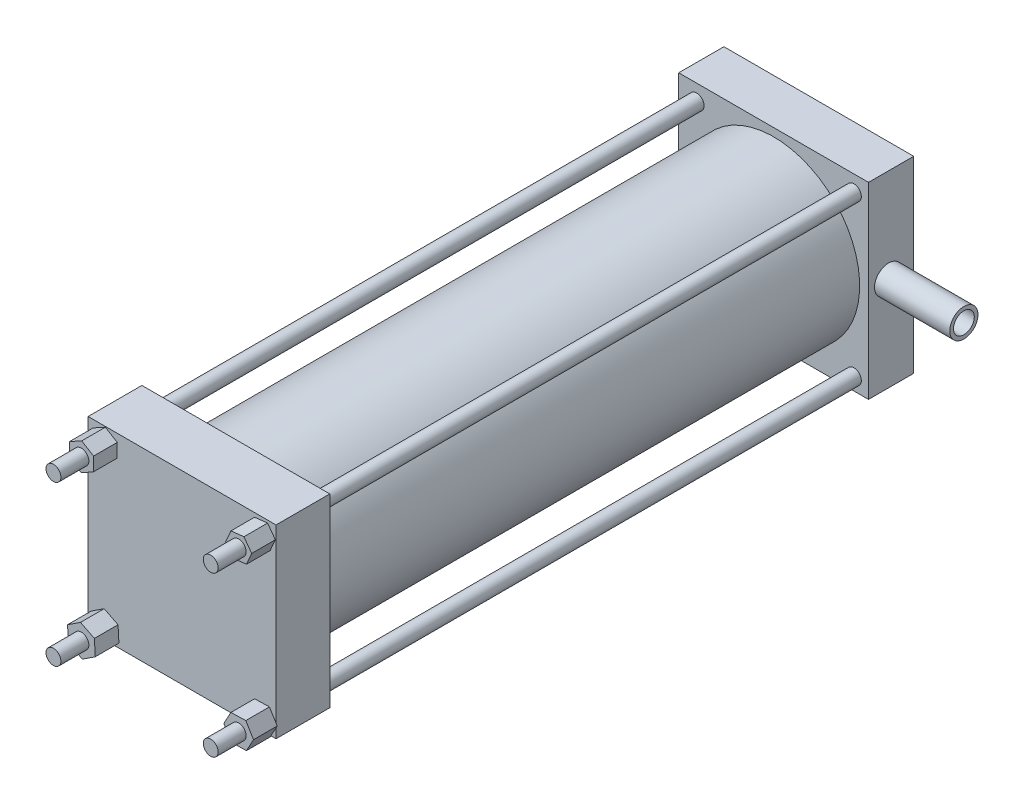
SolidWorks part; units mm, degrees
ref_plane "Front Plane" through (0, 0, 0) normal (0, 0, 1) x (1, 0, 0)
ref_plane "Top Plane" through (0, 0, 0) normal (0, 1, 0) x (1, 0, 0)
ref_plane "Right Plane" through (0, 0, 0) normal (1, 0, 0) x (0, 0, -1)
sketch "Sketch1" plane through (0, 0, 0) normal (0, 0, 1) x (1, 0, 0)
  circle A0 centre (0, 0) radius 30
  circle A1 centre (0, 0) radius 40
  dimension "D1" = 60
  dimension "D2" = 80
extrude "Boss-Extrude1" add sketch "Sketch1" along normal blind 250
ref_plane "Plane1" through (0, 0, 250) normal (0, 0, 1) x (1, 0, 0)
sketch "Sketch2" plane through (0, 0, 250) normal (0, 0, 1) x (1, 0, 0)
  line L1 (-43.6727, 43.0513) -> (43.6727, 43.0513)
  line L2 (-43.6727, 43.0513) -> (-43.6727, -43.0513)
  line L3 (-43.6727, -43.0513) -> (43.6727, -43.0513)
  line L4 (43.6727, 43.0513) -> (43.6727, -43.0513)
  line L5 (-43.6727, 43.0513) -> (43.6727, -43.0513) construction
  line L6 (-43.6727, -43.0513) -> (43.6727, 43.0513) construction
  point P0 (0, 0)
extrude "Boss-Extrude2" add sketch "Sketch2" along normal blind 25
ref_plane "Plane2" through (0, 0, 0) normal (0, 0, -1) x (-1, 0, 0)
sketch "Sketch3" plane through (0, 0, 0) normal (0, 0, -1) x (-1, 0, 0)
  line L1 (-44.1151, 43.6989) -> (44.1151, 43.6989)
  line L2 (-44.1151, 43.6989) -> (-44.1151, -43.6989)
  line L3 (-44.1151, -43.6989) -> (44.1151, -43.6989)
  line L4 (44.1151, 43.6989) -> (44.1151, -43.6989)
  line L5 (-44.1151, 43.6989) -> (44.1151, -43.6989) construction
  line L6 (-44.1151, -43.6989) -> (44.1151, 43.6989) construction
  circle A0 centre (0, 0) radius 15.0552
  point P0 (0, 0)
extrude "Boss-Extrude3" add sketch "Sketch3" along normal blind 21
sketch "Sketch4" plane through (44.1151, 0, 0) normal (1, 0, 0) x (0, 0, -1)
  circle A0 centre (9.3389, 0) radius 6.5589
  circle A1 centre (9.3389, 0) radius 4.8368
extrude "Boss-Extrude4" add sketch "Sketch4" along normal blind 35
sketch "Sketch5" plane through (0, 0, -21) normal (0, 0, -1) x (-1, 0, 0)
  circle A0 centre (-37.3178, 36.2685) radius 3.4633
  circle A1 centre (35.7964, 36.2685) radius 3.4633
  circle A2 centre (35.7964, -37.8077) radius 3.4633
  circle A3 centre (-37.3178, -37.8077) radius 3.4633
extrude "Boss-Extrude5" add sketch "Sketch5" against normal blind 320
sketch "Sketch6" plane through (0, 0, 275) normal (0, 0, 1) x (1, 0, 0)
  line L1 (-30.2671, 32.9214) -> (-30.1331, 39.3835)
  line L2 (-30.1331, 39.3835) -> (-35.6625, 42.7306)
  line L3 (-35.6625, 42.7306) -> (-41.3258, 39.6156)
  line L4 (-41.3258, 39.6156) -> (-41.4597, 33.1535)
  line L5 (-41.4597, 33.1535) -> (-35.9304, 29.8064)
  line L6 (-35.9304, 29.8064) -> (-30.2671, 32.9214)
  line L7 (40.9306, 31.3639) -> (43.3717, 36.945)
  line L8 (43.3717, 36.945) -> (39.7589, 41.8495)
  line L9 (39.7589, 41.8495) -> (33.705, 41.1731)
  line L10 (33.705, 41.1731) -> (31.2639, 35.592)
  line L11 (31.2639, 35.592) -> (34.8767, 30.6875)
  line L12 (34.8767, 30.6875) -> (40.9306, 31.3639)
  line L13 (-29.3509, -41.0426) -> (-29.7722, -33.8432)
  line L14 (-29.7722, -33.8432) -> (-36.2177, -30.6083)
  line L15 (-36.2177, -30.6083) -> (-42.2419, -34.5729)
  line L16 (-42.2419, -34.5729) -> (-41.8207, -41.7723)
  line L17 (-41.8207, -41.7723) -> (-35.3751, -45.0072)
  line L18 (-35.3751, -45.0072) -> (-29.3509, -41.0426)
  line L19 (40.9306, -43.6989) -> (44.2261, -37.6246)
  line L20 (44.2261, -37.6246) -> (40.6133, -31.7334)
  line L21 (40.6133, -31.7334) -> (33.705, -31.9166)
  line L22 (33.705, -31.9166) -> (30.4095, -37.9909)
  line L23 (30.4095, -37.9909) -> (34.0223, -43.8821)
  line L24 (34.0223, -43.8821) -> (40.9306, -43.6989)
  circle A0 centre (-35.7964, 36.2685) radius 5.5975 construction
  circle A1 centre (37.3178, 36.2685) radius 5.2754 construction
  circle A2 centre (-35.7964, -37.8077) radius 6.2456 construction
  circle A3 centre (37.3178, -37.8077) radius 5.9848 construction
extrude "Boss-Extrude6" add sketch "Sketch6" along normal blind 11
